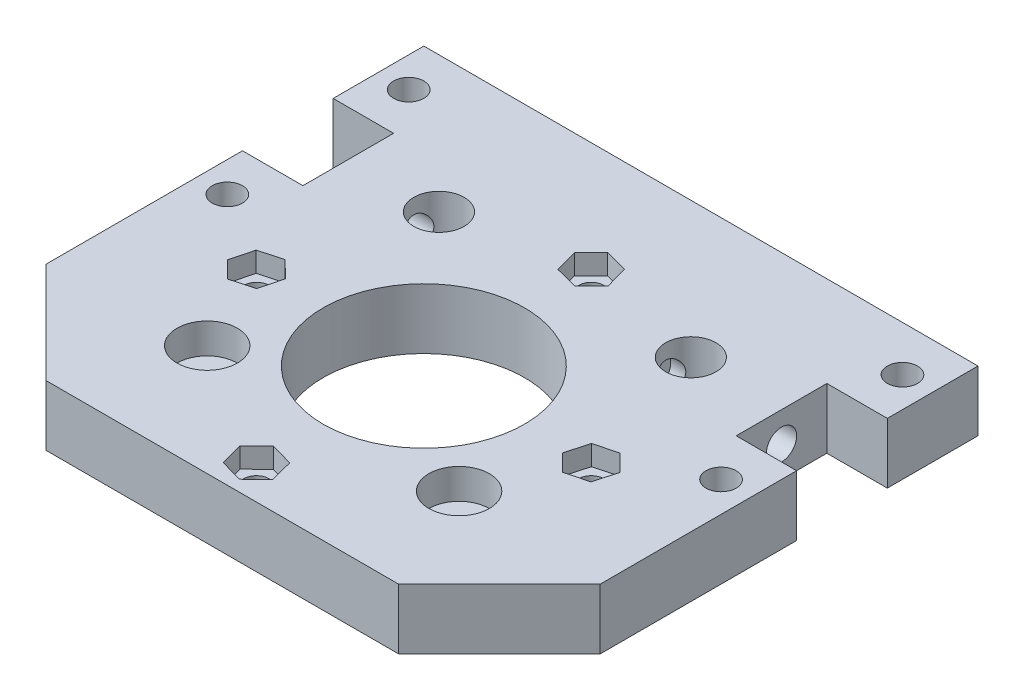
SolidWorks part; units mm, degrees
material "Beech"
ref_plane "Front Plane" through (0, 0, 0) normal (0, 0, 1) x (1, 0, 0)
ref_plane "Top Plane" through (0, 0, 0) normal (0, 1, 0) x (1, 0, 0)
ref_plane "Right Plane" through (0, 0, 0) normal (1, 0, 0) x (0, 0, -1)
sketch "Sketch1" plane through (0, 0, 0) normal (0, 1, 0) x (1, 0, 0)
  line L1 (-33, 25) -> (33, 25)
  line L2 (-33, 25) -> (-33, -70)
  line L3 (-33, -70) -> (33, -70)
  line L4 (33, 25) -> (33, -70)
  circle A0 centre (0, -30) radius 20
  dimension "D6" = 40
  dimension "D1" = 66
  dimension "D2" = 33
  dimension "D3" = 25
  dimension "D4" = 70
  dimension "D5" = 30
extrude "Boss-Extrude1" add sketch "Sketch1" along normal blind 12
sketch "Sketch3" plane through (0, 12, 0) normal (0, 1, 0) x (1, 0, 0)
  line L1 (55, 7) -> (43, 7)
  line L2 (33, 25) -> (33, -70)
  line L3 (43, 7) -> (43, -11)
  line L4 (43, -11) -> (55, -11)
  line L6 (33, -70) -> (55, -70)
  line L7 (55, -70) -> (55, -11)
  line L8 (33, 25) -> (55, 25)
  line L9 (55, 7) -> (55, 25)
  dimension "D1" = 12
  dimension "D2" = 18
  dimension "D3" = 18
  dimension "D4" = 22
extrude "Boss-Extrude3" add sketch "Sketch3" against normal blind 12
mirror "Mirror1" about plane through (0, 0, 0) normal (1, 0, 0) of "Boss-Extrude3"
sketch "Sketch6" plane through (0, 12, 0) normal (0, 1, 0) x (1, 0, 0)
  line L0 (-63.5336, -48) -> (64.8117, -48) construction
  circle A1 centre (-25, -48) radius 6
  circle A2 centre (25, -48) radius 6
  circle A3 centre (0, -30) radius 20 construction
  dimension "D2" = 25
  dimension "D3" = 25
  dimension "D4" = 12
  dimension "D5" = 12
  dimension "D1" = 18
extrude "Cut-Extrude2" cut sketch "Sketch6" against normal blind 6
chamfer "Chamfer1" distance 20 angle 45 2 edges at (55, 6, 70) (-55, 6, 70)
sketch "Sketch7" plane through (0, 12, 0) normal (0, 1, 0) x (1, 0, 0)
  line L0 (-49, 22.071) -> (-49, -31.0852) construction
  line L1 (-59.9918, 16) -> (-35.4854, 16) construction
  line L2 (-63.8876, -20) -> (-39.0752, -20) construction
  line L3 (-55, -11) -> (-43, -11) construction
  line L4 (-42.1899, -2) -> (-20.2042, -2) construction
  line L6 (-43, -11) -> (-43, 7) construction
  circle A0 centre (-49, 16) radius 3
  circle A1 centre (-49, -20) radius 3
  circle A2 centre (-25, -2) radius 5
  dimension "D2" = 6
  dimension "D3" = 6
  dimension "D4" = 18
  dimension "D5" = 10
  dimension "D1" = 9
extrude "Cut-Extrude3" cut sketch "Sketch7" against normal up to next
sketch "Sketch9" plane through (-43, 0, 0) normal (-1, 0, 0) x (0, 0, 1)
  line L0 (11, 12) -> (-7, 12) construction
  line L1 (-7, 0) -> (-7, 12) construction
  circle A0 centre (2, 6) radius 3
  dimension "D1" = 6
  dimension "D2" = 6
  dimension "D3" = 9
extrude "Cut-Extrude5" cut sketch "Sketch9" against normal blind 25
mirror "Mirror2" about plane through (0, 0, 0) normal (1, 0, 0) of "Cut-Extrude5", "Cut-Extrude3"
sketch "Sketch10" plane through (0, 0, 0) normal (0, -1, 0) x (1, 0, 0)
  circle A0 centre (0, 63.234) radius 2.5 construction
  circle A1 centre (-33.234, 30) radius 2.5 construction
  circle A2 centre (0, -3.234) radius 2.5 construction
  circle A3 centre (33.234, 30) radius 2.5 construction
  circle A4 centre (0, 63.234) radius 2.5
  circle A5 centre (-33.234, 30) radius 2.5
  circle A6 centre (0, -3.234) radius 2.5
  circle A7 centre (33.234, 30) radius 2.5
extrude "Cut-Extrude6" cut sketch "Sketch10" against normal up to next
sketch "Sketch12" plane through (0, 12, 0) normal (0, 1, 0) x (1, 0, 0)
  line L1 (3.3343, -59.9549) -> (-1.1727, -58.7069)
  line L2 (-1.1727, -58.7069) -> (-4.5069, -61.986)
  line L3 (-4.5069, -61.986) -> (-3.3343, -66.5132)
  line L4 (-3.3343, -66.5132) -> (1.1727, -67.7611)
  line L5 (1.1727, -67.7611) -> (4.5069, -64.482)
  line L6 (4.5069, -64.482) -> (3.3343, -59.9549)
  line L7 (-29.8998, -33.2791) -> (-28.7271, -28.752)
  line L8 (-28.7271, -28.752) -> (-32.0613, -25.4729)
  line L9 (-32.0613, -25.4729) -> (-36.5683, -26.7209)
  line L10 (-36.5683, -26.7209) -> (-37.741, -31.248)
  line L11 (-37.741, -31.248) -> (-34.4067, -34.5271)
  line L12 (-34.4067, -34.5271) -> (-29.8998, -33.2791)
  line L13 (-3.2828, -0.0967) -> (1.2431, -1.2743)
  line L14 (1.2431, -1.2743) -> (4.5258, 2.0564)
  line L15 (4.5258, 2.0564) -> (3.2828, 6.5647)
  line L16 (3.2828, 6.5647) -> (-1.2431, 7.7423)
  line L17 (-1.2431, 7.7423) -> (-4.5258, 4.4116)
  line L18 (-4.5258, 4.4116) -> (-3.2828, -0.0967)
  line L19 (29.9513, -26.6693) -> (28.7082, -31.1776)
  line L20 (28.7082, -31.1776) -> (31.9909, -34.5083)
  line L21 (31.9909, -34.5083) -> (36.5168, -33.3307)
  line L22 (36.5168, -33.3307) -> (37.7599, -28.8224)
  line L23 (37.7599, -28.8224) -> (34.4771, -25.4917)
  line L24 (34.4771, -25.4917) -> (29.9513, -26.6693)
  circle A0 centre (0, -63.234) radius 4.05 construction
  circle A1 centre (-33.234, -30) radius 4.05 construction
  circle A2 centre (0, 3.234) radius 4.05 construction
  circle A3 centre (33.234, -30) radius 4.05 construction
  dimension "D1" = 8.1
  dimension "D2" = 8.1
  dimension "D3" = 8.1
  dimension "D4" = 8.1
extrude "Cut-Extrude7" cut sketch "Sketch12" against normal blind 4
